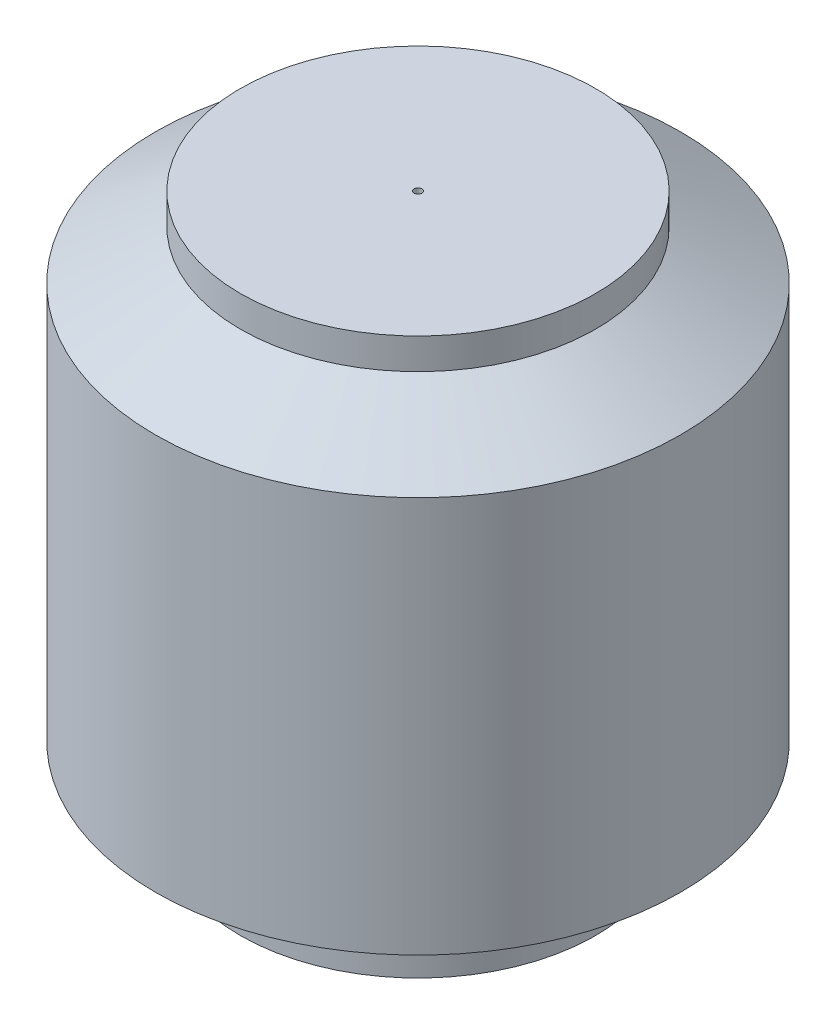
SolidWorks part; units mm, degrees
material "Pure Silver"
ref_plane "Front Plane" through (0, 0, 0) normal (0, 0, 1) x (1, 0, 0)
ref_plane "Top Plane" through (0, 0, 0) normal (0, 1, 0) x (1, 0, 0)
ref_plane "Right Plane" through (0, 0, 0) normal (1, 0, 0) x (0, 0, -1)
sketch "Sketch1" plane through (0, 0, 0) normal (0, 0, 1) x (1, 0, 0)
  line L0 (0, 52.509) -> (0, -90.8912) construction
  line L1 (0, 0) -> (-57.5, 0)
  line L2 (-57.5, 0) -> (-57.5, -10)
  line L3 (-57.5, -10) -> (-85, -25.8771)
  line L4 (-85, -25.8771) -> (-85, -154.1229)
  line L5 (-85, -154.1229) -> (-57.5, -170)
  line L6 (-57.5, -170) -> (-57.5, -180)
  line L7 (-57.5, -180) -> (0, -180)
  line L8 (0, -180) -> (0, 0)
  dimension "D1" = 85
  dimension "D2" = 57.5
  dimension "D3" = 10
  dimension "D4" = 120
  dimension "D5" = 120
  dimension "D6" = 180
revolve "Revolve1" add sketch "Sketch1" angle 360 about L0
sketch "Sketch2" plane through (0, 0, 0) normal (0, 1, 0) x (1, 0, 0)
  circle A0 centre (0, 0) radius 1.25
  dimension "D1" = 2.5
extrude "Cut-Extrude1" cut sketch "Sketch2" against normal through all
chamfer "Chamfer1" distance 2 angle 45 1 edges at (0, -180, 1.25)
sketch "Sketch3" [suppressed] plane through (0, -180, 0) normal (0, -1, 0) x (1, 0, 0)
  circle A0 centre (0, 0) radius 1
  dimension "D1" = 2
sketch "Sketch4" [suppressed] plane through (0, 0, 0) normal (0, 0, 1) x (1, 0, 0)
  line L0 (0, -180) -> (0, -126.6987)
  line L1 (57.5, 0) -> (-57.5, 0) construction
  line L2 (-10, -84.0192) -> (-10, -95.9808)
  line L3 (-10, -90) -> (-85, -90) construction
  line L4 (-85, -25.8771) -> (-85, -154.1229) construction
  line L5 (-7.9904, -76.5192) -> (-4.6891, -70.8013)
  line L6 (-7.9904, -103.4808) -> (-4.6891, -109.1987)
  line L7 (0, -53.3013) -> (0, 0)
  arc A0 (0, -53.3013) -> (-4.6891, -70.8013) centre (-35, -53.3013) cw
  arc A1 (0, -126.6987) -> (-4.6891, -109.1987) centre (-35, -126.6987) ccw
  arc A2 (-10, -84.0192) -> (-7.9904, -76.5192) centre (5, -84.0192) cw
  arc A3 (-7.9904, -103.4808) -> (-10, -95.9808) centre (5, -95.9808) cw
  point P20 (-10, -80)
  point P23 (-10, -100)
  dimension "D5" = 35
  dimension "D6" = 35
  dimension "D7" = 15
  dimension "D8" = 15
  dimension "D1" = 10
  dimension "D2" = 20
  dimension "D3" = 30
  dimension "D4" = 30
sweep "Cut-Sweep1" [suppressed] cut profiles "Sketch3" path "Sketch4"
